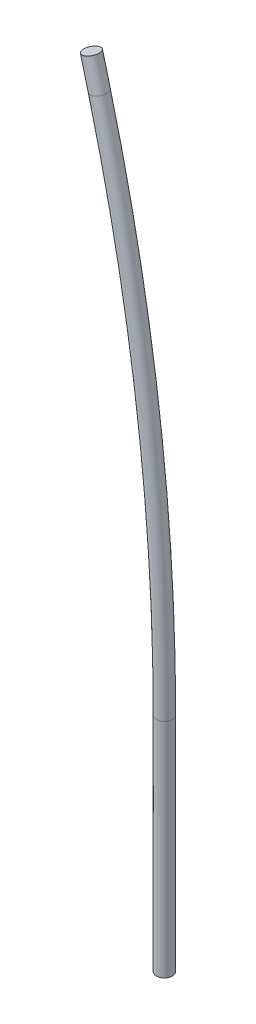
SolidWorks part; units mm, degrees
material "Nylon 101"
ref_plane "Front Plane" through (0, 0, 0) normal (0, 0, 1) x (1, 0, 0)
ref_plane "Top Plane" through (0, 0, 0) normal (0, 1, 0) x (1, 0, 0)
ref_plane "Right Plane" through (0, 0, 0) normal (1, 0, 0) x (0, 0, -1)
sketch "Sketch1" plane through (0, 0, 0) normal (0, 0, 1) x (1, 0, 0)
  line L0 (41.275, 0) -> (41.275, -18.7688) construction
  line L1 (0, 0) -> (0, 136.5906) construction
  arc A0 (41.275, 0) -> (15.24, 203.2) centre (-764.7181, 0) ccw
  dimension "D1" = 41.275
  dimension "D2" = 15.24
  dimension "D3" = 203.2
sketch "Sketch2" plane through (0, 0, 0) normal (0, 1, 0) x (1, 0, 0)
  line L0 (15.24, 0) -> (41.275, 0) construction
  circle A0 centre (41.275, 0) radius 3.175
  dimension "D1" = 6.35
  dimension "D2" = 41.275
sweep "Sweep1" add profiles "Sketch2" path "Sketch1"
sketch "Sketch4" plane through (-48.6056, 186.5665, 0) normal (-0.2521, 0.9677, 0) x (0.9677, 0.2521, 0)
  circle A0 centre (65.9767, 0) radius 3.175
  dimension "D1" = 6.35
  dimension "D2" = 65.9767
extrude "Boss-Extrude1" add sketch "Sketch4" along normal blind 12.7
sketch "Sketch5" plane through (0, 0, 0) normal (0, -1, 0) x (1, 0, 0)
  circle A0 centre (41.275, 0) radius 3.175
  dimension "D2" = 6.35
  dimension "D1" = 41.275
extrude "Boss-Extrude2" add sketch "Sketch5" along normal blind 88.9
